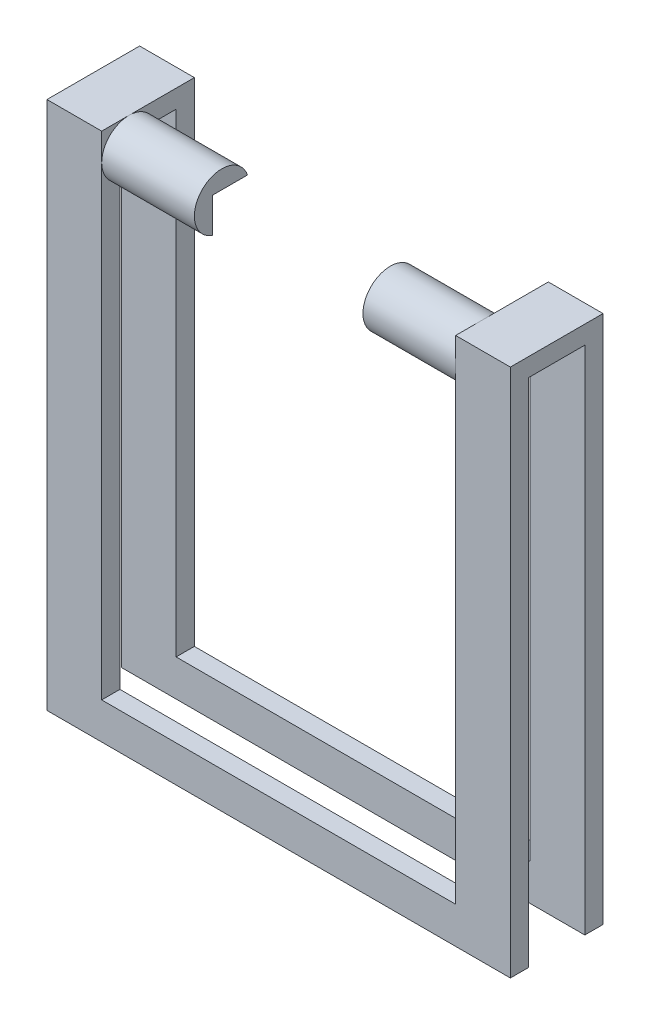
SolidWorks part; units mm, degrees
ref_plane "Front Plane" through (0, 0, 0) normal (0, 0, 1) x (1, 0, 0)
ref_plane "Top Plane" through (0, 0, 0) normal (0, 1, 0) x (1, 0, 0)
ref_plane "Right Plane" through (0, 0, 0) normal (1, 0, 0) x (0, 0, -1)
sketch "Sketch1" plane through (0, 0, 0) normal (0, 1, 0) x (1, 0, 0)
  line L1 (-12.7, -2.54) -> (12.7, -2.54)
  line L2 (-12.7, -2.54) -> (-12.7, 2.54)
  line L3 (-12.7, 2.54) -> (12.7, 2.54)
  line L4 (12.7, -2.54) -> (12.7, 2.54)
  line L5 (-12.7, -2.54) -> (12.7, 2.54) construction
  line L6 (-12.7, 2.54) -> (12.7, -2.54) construction
  point P0 (0, 0)
  dimension "D1" = 25.4
  dimension "D2" = 5.08
extrude "Boss-Extrude1" add sketch "Sketch1" along normal blind 2
sketch "Sketch2" plane through (0, 2, 0) normal (0, 1, 0) x (1, 0, 0)
  line L0 (-12.7, -2.54) -> (12.7, -2.54) construction
  line L1 (12.7, 2.54) -> (9.7, 2.54)
  line L2 (12.7, 2.54) -> (12.7, -2.54)
  line L3 (12.7, -2.54) -> (9.7, -2.54)
  line L4 (9.7, 2.54) -> (9.7, -2.54)
  dimension "D1" = 3
extrude "Boss-Extrude2" add sketch "Sketch2" along normal blind 27
sketch "Sketch3" plane through (9.7, 0, 0) normal (-1, 0, 0) x (0, 0, 1)
  line L0 (-2.54, 29) -> (2.54, 29) construction
  line L1 (2.54, 29) -> (2.54, 2) construction
  circle A0 centre (1.04, 27.5) radius 1.5
  dimension "D1" = 3
extrude "Boss-Extrude3" add sketch "Sketch3" along normal blind 5.08
mirror "Mirror1" about plane through (0, 0, 0) normal (1, 0, 0) of "Boss-Extrude2", "Boss-Extrude3"
sketch "Sketch4" plane through (-12.7, 0, 0) normal (-1, 0, 0) x (0, 0, 1)
  line L5 (-2.54, 0) -> (2.54, 0) construction
  line L8 (-1.54, 1) -> (1.54, 1)
  line L9 (1.54, 1) -> (1.54, 28)
  line L10 (1.54, 28) -> (-1.54, 28)
  line L11 (-1.54, 28) -> (-1.54, 1)
  line L12 (-1.54, 0) -> (1.54, 0)
  line L13 (1.54, 0) -> (1.54, 28)
  line L14 (1.54, 28) -> (-1.54, 28)
  line L15 (-1.54, 28) -> (-1.54, 0)
  dimension "D1" = 1
extrude "Cut-Extrude1" cut sketch "Sketch4" against normal through all both and the other way through all
